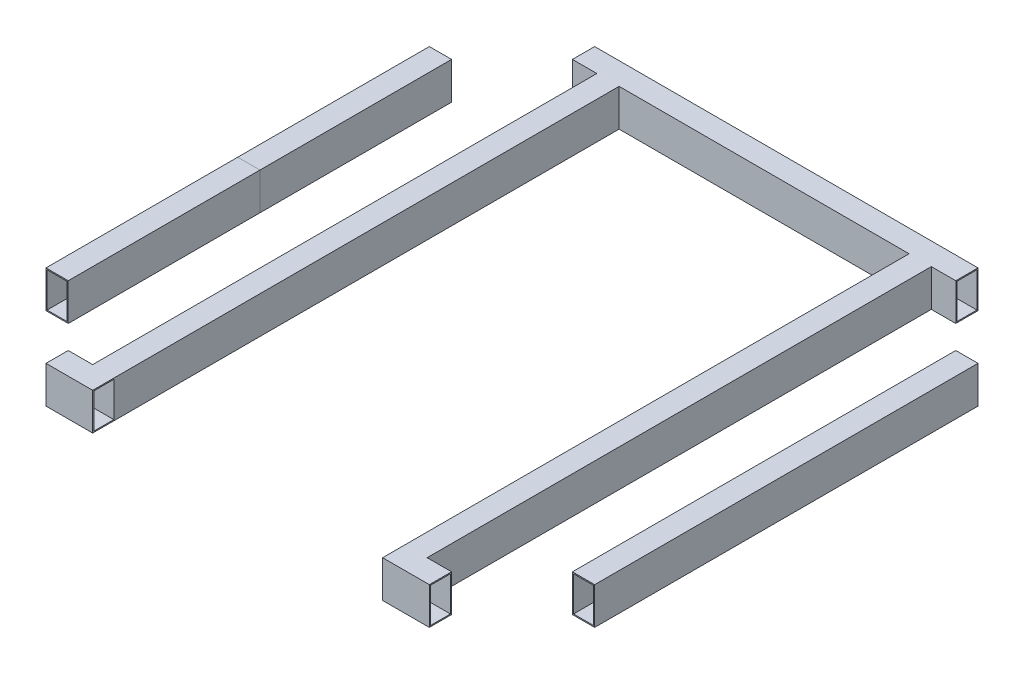
SolidWorks part; units mm, degrees
other "Marcação1"
sketch "Esboço9" plane through (-370, 25, 370) normal (-0.2888, 0.859, 0.4228) x (0.9564, 0.2784, 0.0877)
sketch "Esboço10" plane through (-370, 25, 370) normal (-0.2888, 0.859, 0.4228) x (0.9564, 0.2784, 0.0877)
sketch "Esboço11" plane through (-370, 25, 370) normal (-0.2888, 0.859, 0.4228) x (0.9564, 0.2784, 0.0877)
material "201 Aço inoxidável recozido (SS)"
ref_plane "Plano frontal" through (0, 0, 0) normal (0, 0, 1) x (1, 0, 0)
ref_plane "Plano superior" through (0, 0, 0) normal (0, 1, 0) x (1, 0, 0)
ref_plane "Plano direito" through (0, 0, 0) normal (1, 0, 0) x (0, 0, -1)
sketch "Esboço1" plane through (0, 0, 0) normal (0, 1, 0) x (1, 0, 0)
  line L1 (-355, -355) -> (355, -355)
  line L2 (-355, -355) -> (-355, 355)
  line L3 (-355, 355) -> (355, 355)
  line L4 (355, -355) -> (355, 355)
  line L5 (-355, -355) -> (355, 355) construction
  line L6 (-355, 355) -> (355, -355) construction
  point P0 (0, 0)
  dimension "D1" = 710
  dimension "D2" = 710
sketch "Esboço2" plane through (0, 0, 0) normal (0, 0, 1) x (1, 0, 0)
  line L0 (-355, 0) -> (355, 0) construction
  line L1 (-370, -25) -> (-340, -25)
  line L2 (-370, -25) -> (-370, 25)
  line L3 (-370, 25) -> (-340, 25)
  line L4 (-340, -25) -> (-340, 25)
  line L5 (-370, -25) -> (-340, 25) construction
  line L6 (-370, 25) -> (-340, -25) construction
  line L7 (-355, 0) -> (355, 0) construction
  line L8 (-368.5, 23.5) -> (-341.5, 23.5)
  line L9 (-341.5, -23.5) -> (-341.5, 23.5)
  line L10 (-368.5, -23.5) -> (-341.5, -23.5)
  line L11 (-368.5, -23.5) -> (-368.5, 23.5)
  point P0 (-355, 0)
  dimension "D1" = 30
  dimension "D2" = 50
  dimension "D3" = 1.5
sweep "Varredura1" add profiles "Esboço2" path "Esboço1"
sketch "Esboço3" plane through (0, 25, 0) normal (0, 1, 0) x (1, 0, 0)
  line L1 (-481.5, 481.5) -> (-258.5, 481.5)
  line L2 (-481.5, 481.5) -> (-481.5, 258.5)
  line L3 (-481.5, 258.5) -> (-258.5, 258.5)
  line L4 (-258.5, 481.5) -> (-258.5, 258.5)
  line L5 (-481.5, 481.5) -> (-258.5, 258.5) construction
  line L6 (-481.5, 258.5) -> (-258.5, 481.5) construction
  line L7 (481.5, 481.5) -> (258.5, 481.5)
  line L8 (481.5, 481.5) -> (481.5, 258.5)
  line L9 (481.5, 258.5) -> (258.5, 258.5)
  line L10 (258.5, 481.5) -> (258.5, 258.5)
  line L11 (481.5, 481.5) -> (258.5, 258.5) construction
  line L12 (481.5, 258.5) -> (258.5, 481.5) construction
  line L13 (481.5, -481.5) -> (258.5, -481.5)
  line L14 (481.5, -481.5) -> (481.5, -258.5)
  line L15 (481.5, -258.5) -> (258.5, -258.5)
  line L16 (258.5, -481.5) -> (258.5, -258.5)
  line L17 (481.5, -481.5) -> (258.5, -258.5) construction
  line L18 (481.5, -258.5) -> (258.5, -481.5) construction
  line L19 (-481.5, -481.5) -> (-258.5, -481.5)
  line L20 (-481.5, -481.5) -> (-481.5, -258.5)
  line L21 (-481.5, -258.5) -> (-258.5, -258.5)
  line L22 (-258.5, -481.5) -> (-258.5, -258.5)
  line L23 (-481.5, -481.5) -> (-258.5, -258.5) construction
  line L24 (-481.5, -258.5) -> (-258.5, -481.5) construction
  point P0 (-370, 370)
  point P6 (370, 370)
  point P12 (370, -370)
  point P18 (-370, -370)
  dimension "D1" = 223
  dimension "D2" = 223
  dimension "D3" = 223
  dimension "D4" = 223
  dimension "D5" = 223
  dimension "D6" = 223
  dimension "D7" = 223
  dimension "D8" = 223
extrude "Corte-extrusão1" cut sketch "Esboço3" against normal mid plane 370
sketch "Esboço4" plane through (0, 0, 0) normal (0, 1, 0) x (1, 0, 0)
  line L0 (-210.54, 340) -> (-210.54, -340)
  line L1 (-258.5, 340) -> (258.5, 340) construction
  line L2 (258.5, -340) -> (-258.5, -340) construction
  dimension "D1" = 210.54
sketch "Esboço6" plane through (0, 0, 0) normal (0, 0, 1) x (1, 0, 0)
  line L0 (258.5, 25) -> (-258.5, 25) construction
  line L1 (-225.54, -25) -> (-195.54, -25)
  line L2 (-225.54, -25) -> (-225.54, 25)
  line L3 (-225.54, 25) -> (-195.54, 25)
  line L4 (-195.54, -25) -> (-195.54, 25)
  line L5 (-225.54, -25) -> (-195.54, 25) construction
  line L6 (-225.54, 25) -> (-195.54, -25) construction
  point P0 (-210.54, 0)
  point P1 (-210.54, 0)
  dimension "D1" = 210.54
  dimension "D2" = 30
  dimension "D3" = 50
sweep "Varredura2" add profiles "Esboço6" path "Esboço4"
sketch "Esboço7" plane through (0, 0, 0) normal (0, 1, 0) x (1, 0, 0)
  line L0 (210.54, 340) -> (210.54, -340)
  line L1 (-195.54, 340) -> (258.5, 340) construction
  line L2 (258.5, -340) -> (-195.54, -340) construction
  dimension "D1" = 210.54
sketch "Esboço8" plane through (0, 0, 0) normal (0, 0, 1) x (1, 0, 0)
  line L0 (258.5, 25) -> (-258.5, 25) construction
  line L1 (195.54, -25) -> (225.54, -25)
  line L2 (195.54, -25) -> (195.54, 25)
  line L3 (195.54, 25) -> (225.54, 25)
  line L4 (225.54, -25) -> (225.54, 25)
  line L5 (195.54, -25) -> (225.54, 25) construction
  line L6 (195.54, 25) -> (225.54, -25) construction
  point P0 (210.54, 0)
  dimension "D1" = 50
  dimension "D2" = 30
  dimension "D3" = 210.54
sweep "Varredura3" add profiles "Esboço8" path "Esboço7"
sketch "Esboço13" plane through (0, 25, 0) normal (0, 1, 0) x (1, 0, 0)
  line L0 (195.54, -340) -> (-195.54, -340) construction
  line L1 (-195.54, -340) -> (195.54, -340)
  line L2 (-195.54, -340) -> (-195.54, -370)
  line L3 (-195.54, -370) -> (195.54, -370)
  line L4 (195.54, -340) -> (195.54, -370)
  line L5 (258.5, -370) -> (-258.5, -370) construction
  line L6 (-225.54, -340) -> (-225.54, 340) construction
  line L7 (225.54, -340) -> (225.54, 340) construction
  dimension "D1" = 30
  dimension "D2" = 30
extrude "Corte-extrusão3" cut sketch "Esboço13" against normal blind 92
equation "\"D3@Esboço3\"=\"D2@Esboço3\""
equation "\"D4@Esboço3\"=\"D1@Esboço3\""
equation "\"D6@Esboço3\"=\"D2@Esboço3\""
equation "\"D5@Esboço3\"=\"D1@Esboço3\""
equation "\"D7@Esboço3\"=\"D2@Esboço3\""
equation "\"D8@Esboço3\"=\"D1@Esboço3\""
